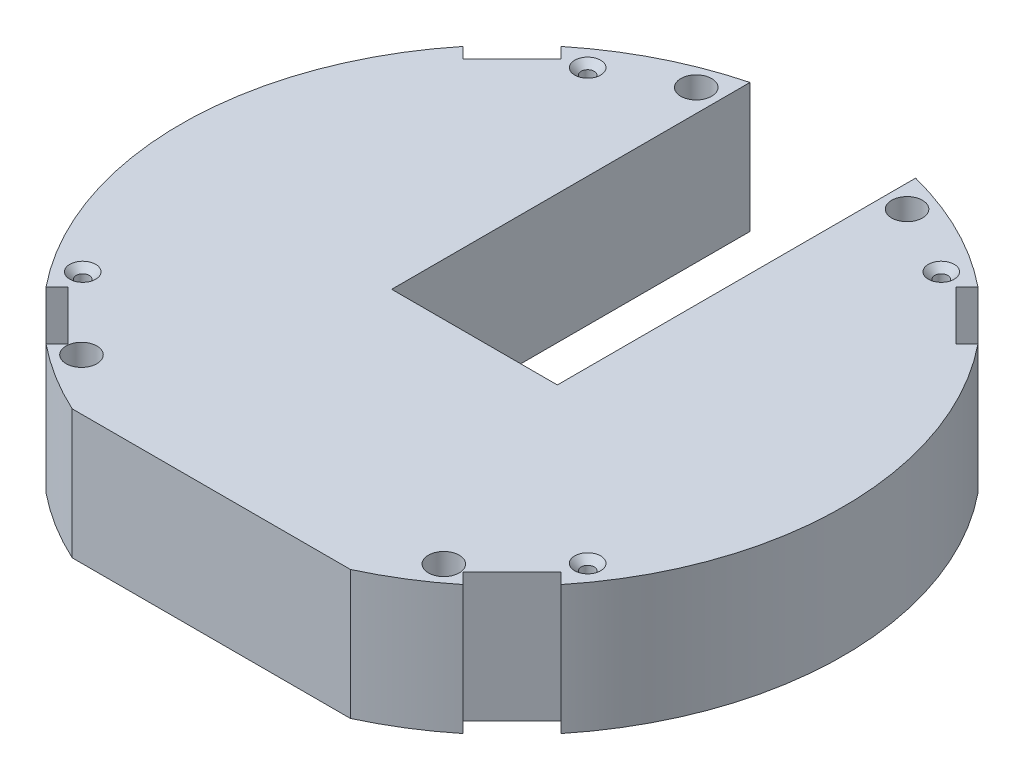
SolidWorks part; units mm, degrees
ref_plane "Plano frontal" through (0, 0, 0) normal (0, 0, 1) x (1, 0, 0)
ref_plane "Plano superior" through (0, 0, 0) normal (0, 1, 0) x (1, 0, 0)
ref_plane "Plano direito" through (0, 0, 0) normal (1, 0, 0) x (0, 0, -1)
sketch "Esboço3" plane through (0, 0, 0) normal (0, 1, 0) x (1, 0, 0)
  line L0 (-21.5, 83.2691) -> (-21.5, -9.7309)
  line L1 (-21.5, -9.7309) -> (21.5, -9.7309)
  line L2 (21.5, 83.2691) -> (21.5, -9.7309)
  line L3 (0, 0) -> (0, -78.0563) construction
  line L4 (-36.1, -78.0563) -> (36.1, -78.0563)
  line L5 (-60.4773, 60.4773) -> (60.4773, -60.4773) construction
  line L7 (-66.8412, 54.1133) -> (-54.1133, 66.8412)
  line L8 (-66.8412, -54.1133) -> (-54.1133, -66.8412)
  line L9 (66.8412, -54.1133) -> (54.1133, -66.8412)
  line L10 (66.8412, 54.1133) -> (54.1133, 66.8412)
  line L11 (60.4773, 60.4773) -> (-60.4773, -60.4773) construction
  arc A0 (-21.5, 83.2691) -> (-54.1133, 66.8412) centre (0, 0) ccw
  arc A1 (36.1, -78.0563) -> (54.1133, -66.8412) centre (0, 0) ccw
  arc A2 (-66.8412, 54.1133) -> (-66.8412, -54.1133) centre (0, 0) ccw
  arc A3 (-54.1133, -66.8412) -> (-36.1, -78.0563) centre (0, 0) ccw
  arc A4 (66.8412, -54.1133) -> (66.8412, 54.1133) centre (0, 0) ccw
  arc A5 (54.1133, 66.8412) -> (21.5, 83.2691) centre (0, 0) ccw
  point P8 (0, -9.7309)
  point P12 (0, -78.0563)
  point P21 (-60.4773, -60.4773)
  point P22 (-60.4773, 60.4773)
  dimension "D1" = 172
  dimension "D2" = 93
  dimension "D3" = 21.5
  dimension "D4" = 36.1
  dimension "D5" = 45
  dimension "D6" = 9
  dimension "D7" = 9
  dimension "D8" = 45
extrude "Ressalto-extrusão2" add sketch "Esboço3" along normal blind 33.5
hole_wizard "Escareado para SFHCS M31" positions "Esboço4" profile "Esboço6" countersink size "M3" standard "Ansi Metric" end condition through all
sketch "Esboço4" plane through (0, 33.5, 0) normal (0, 1, 0) x (1, 0, 0)
  line L0 (45.8861, 65.5322) -> (0, 0) construction
  line L1 (0, 0) -> (65.5322, -45.8861) construction
  line L3 (0, 0) -> (0, 37.6964) construction
  point P0 (45.8861, 65.5322)
  point P2 (65.5322, -45.8861)
  point P19 (-65.5322, -45.8861)
  point P20 (-45.8861, 65.5322)
  dimension "D1" = 35
  dimension "D2" = 55
  dimension "D3" = 80
  dimension "D4" = 80
sketch "Esboço6" plane through (45.8861, 33.5, -65.5322) normal (1, 0, 0) x (0, 0, 1)
  line L0 (0, 0) -> (0, 33.5)
  line L1 (0, 33.5) -> (1.7, 33.5)
  line L2 (1.7, 33.5) -> (1.7, 1.66)
  line L3 (1.7, 1.66) -> (3.36, 0)
  line L5 (3.36, 0) -> (0, 0)
  line L6 (-1.7, 1.66) -> (-3.36, 0) construction
  line L11 (0, -6.35) -> (0, 107.95) construction
  dimension "Thru Hole Dia." = 3.4
  dimension "Thru Hole Depth" = 33.5
  dimension "Near C'Sink Dia." = 6.72
  dimension "Near C'Sink Angle" = 90
sketch "Esboço7" plane through (0, 33.5, 0) normal (0, 1, 0) x (1, 0, 0)
  line L0 (0, 0) -> (-27.3616, 75.1754) construction
  line L1 (0, 0) -> (-47.0228, -64.7214) construction
  line L2 (0, 0) -> (0, 39.0312) construction
  circle A0 centre (-27.3616, 75.1754) radius 4
  circle A1 centre (-47.0228, -64.7214) radius 4
  circle A2 centre (47.0228, -64.7214) radius 4
  circle A3 centre (27.3616, 75.1754) radius 4
  point P7 (27.3616, 75.1754)
  dimension "D1" = 8
  dimension "D2" = 8
  dimension "D3" = 20
  dimension "D4" = 36
  dimension "D5" = 80
  dimension "D6" = 80
extrude "Corte-extrusão1" cut sketch "Esboço7" against normal through all
sketch "Esboço9" plane through (0, 33.5, 0) normal (0, 1, 0) x (1, 0, 0)
  line L0 (-66.8412, -54.1133) -> (-54.1133, -66.8412)
  line L1 (-54.1133, -66.8412) -> (-51.2849, -64.0128)
  line L2 (-51.2849, -64.0128) -> (-64.0128, -51.2849)
  line L3 (-64.0128, -51.2849) -> (-66.8412, -54.1133)
  line L4 (0, 0) -> (0, 49.0337) construction
  line L5 (0, 0) -> (117.9037, 0) construction
  line L6 (51.2849, -64.0128) -> (64.0128, -51.2849)
  line L7 (54.1133, -66.8412) -> (51.2849, -64.0128)
  line L8 (66.8412, -54.1133) -> (54.1133, -66.8412)
  line L9 (64.0128, -51.2849) -> (66.8412, -54.1133)
  line L10 (54.1133, 66.8412) -> (51.2849, 64.0128)
  line L11 (66.8412, 54.1133) -> (54.1133, 66.8412)
  line L12 (64.0128, 51.2849) -> (66.8412, 54.1133)
  line L13 (51.2849, 64.0128) -> (64.0128, 51.2849)
  line L14 (-51.2849, 64.0128) -> (-64.0128, 51.2849)
  line L15 (-54.1133, 66.8412) -> (-51.2849, 64.0128)
  line L16 (-66.8412, 54.1133) -> (-54.1133, 66.8412)
  line L17 (-64.0128, 51.2849) -> (-66.8412, 54.1133)
  dimension "D1" = 4
extrude "Corte-extrusão2" cut sketch "Esboço9" against normal through all
